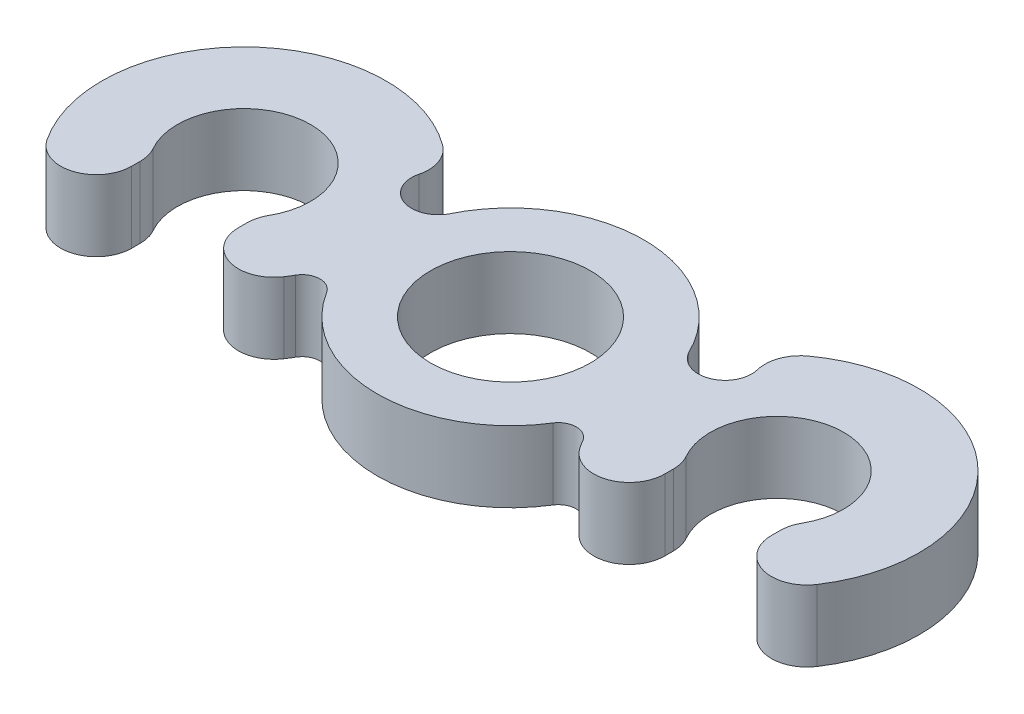
SolidWorks part; units mm, degrees
material "PE hochdicht"
ref_plane "Ebene vorne" through (0, 0, 0) normal (0, 0, 1) x (1, 0, 0)
ref_plane "Ebene oben" through (0, 0, 0) normal (0, 1, 0) x (1, 0, 0)
ref_plane "Ebene rechts" through (0, 0, 0) normal (1, 0, 0) x (0, 0, -1)
sketch "Skizze1" plane through (0, 0, 0) normal (0, 1, 0) x (1, 0, 0)
  line L0 (-15, 0) -> (0, 0) construction
  line L1 (-7.5838, -3) -> (0, -3)
  line L2 (-8.0718, 4) -> (0, 4)
  line L3 (0, 4) -> (0, -3)
  line L4 (-15, 4) -> (0, 4) construction
  line L5 (-15, -3) -> (0, -3) construction
  circle A0 centre (-15, 0) radius 3.75
  arc A1 (-8.0718, 4) -> (-7.5838, -3) centre (-15, 0) ccw
  dimension "D3" = 8
  dimension "D4" = 7.5
  dimension "D5" = 15
  dimension "D1" = 3
  dimension "D2" = 4
extrude "Aufsatz-Linear austragen1" add sketch "Skizze1" along normal mid plane 4
sketch "Skizze2" plane through (0, 2, 0) normal (0, 1, 0) x (1, 0, 0)
  line L0 (-15, 0) -> (-15, -8) construction
  line L1 (-12, 0) -> (-12, -8)
  line L2 (-18, 0) -> (-18, -8)
  circle A0 centre (-8.0718, 4) radius 1.5
  arc A1 (-8.0718, 4) -> (-7.5838, -3) centre (-15, 0) ccw construction
  arc A2 (-12, 0) -> (-18, 0) centre (-15, 0) ccw
  arc A3 (-18, -8) -> (-12, -8) centre (-15, -8) ccw
  point P10 (-15, -4)
  dimension "D1" = 3
  dimension "D2" = 6
extrude "Schnitt-Linear austragen1" cut sketch "Skizze2" against normal through all
fillet "Verrundung1" radius 2 5 edges at (-18, 0, 2.25) (-12, 0, 2.25) (-6.5718, 0, -4) (-8.9403, 0, -5.223) (-7.5838, 0, 3)
fillet "Verrundung2" radius 2 2 edges at (-12, 0, 7.4162) (-18, 0, 7.4162)
sketch "Skizze3" plane through (0, 0, 0) normal (0, 0, 1) x (1, 0, 0)
  line L0 (0, 0) -> (-4.0718, 0)
  line L1 (0, 2) -> (0, -2) construction
  line L2 (-8.3333, 2) -> (-12, 2) construction
  line L4 (-8.0718, 2) -> (0, 2)
  line L5 (0, 2) -> (0, 0)
  arc A0 (-4.0718, 0) -> (-8.0718, 2) centre (-4.0718, 5) cw
  dimension "D1" = 5
extrude "Schnitt-Linear austragen2" [suppressed] cut sketch "Skizze3" against normal mid plane 5
fillet "Verrundung3" [suppressed] radius 1
mirror "Spiegeln1" about plane through (0, 2, -4) normal (-1, 0, 0) of bodies 103 104
sketch "Skizze4" plane through (0, 2, 0) normal (0, 1, 0) x (1, 0, 0)
  circle A0 centre (0, 0) radius 7.5085
  arc A4 (-9.5269, 4.3641) -> (-6.8408, 3.1429) centre (-8.0718, 4) ccw construction
extrude "Aufsatz-Linear austragen2" add sketch "Skizze4" against normal up to surface (4 mm away) up to face at (0, -2, 0.4849)
sketch "Skizze5" plane through (0, 2, 0) normal (0, 1, 0) x (1, 0, 0)
  circle A0 centre (0, 0) radius 4.5
  dimension "D1" = 9
extrude "Schnitt-Linear austragen3" cut sketch "Skizze5" against normal through all
fillet "Verrundung4" radius 1 2 edges at (6.8535, 0, 3.0671) (-6.8535, 0, 3.0671)
